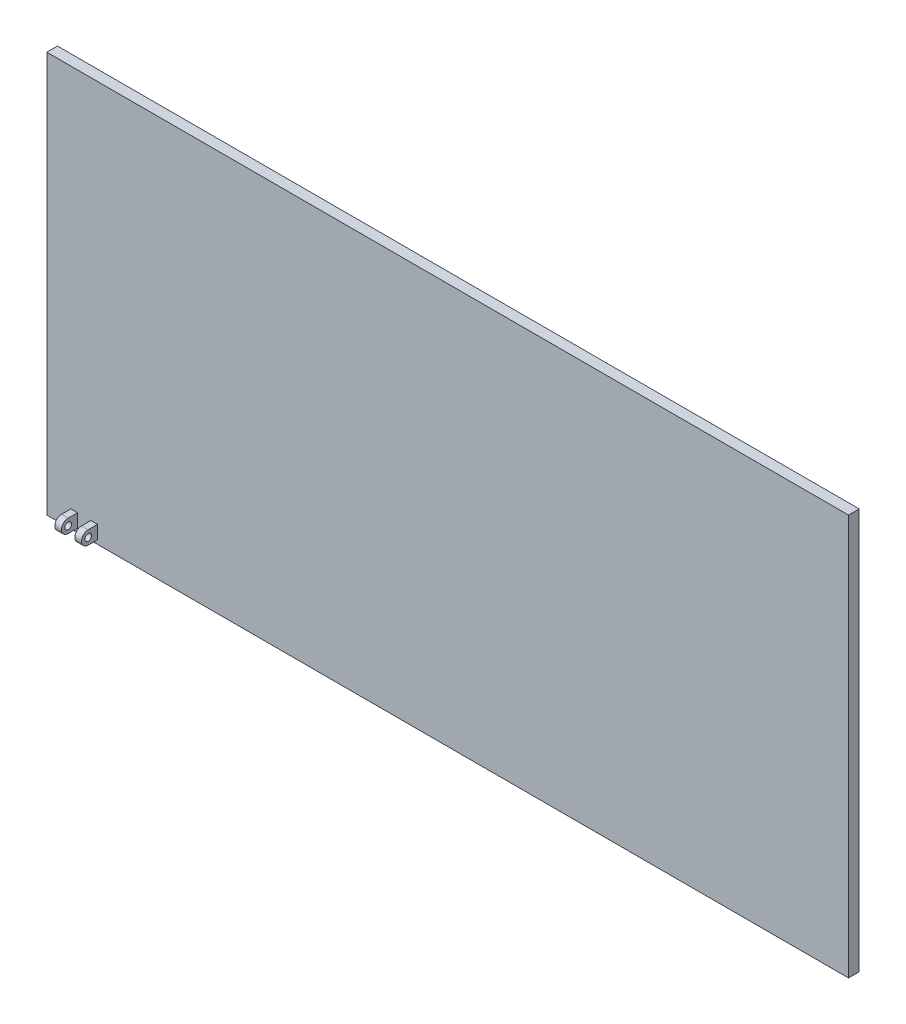
SolidWorks part; units mm, degrees
ref_plane "Plan de face" through (0, 0, 0) normal (0, 0, 1) x (1, 0, 0)
ref_plane "Plan de dessus" through (0, 0, 0) normal (0, 1, 0) x (1, 0, 0)
ref_plane "Plan de droite" through (0, 0, 0) normal (1, 0, 0) x (0, 0, -1)
sketch "Esquisse1" plane through (0, 0, 0) normal (0, 0, 1) x (1, 0, 0)
  line L1 (0, 0) -> (3000, 0)
  line L2 (0, 0) -> (0, 1500)
  line L3 (0, 1500) -> (3000, 1500)
  line L4 (3000, 0) -> (3000, 1500)
  dimension "D1" = 3000
  dimension "2000" = 1500
extrude "Boss.-Extru.1" add sketch "Esquisse1" along normal mid plane 40
sketch "Esquisse3" plane through (0, 0, 0) normal (1, 0, 0) x (0, 0, -1)
  line L0 (-20, 57.735) -> (-20, 0)
  line L1 (-20, 57.735) -> (880, -461.8802)
  line L2 (-20, 0) -> (880, -519.6152)
  line L3 (880, -461.8802) -> (880, -519.6152)
  line L4 (-20, 0) -> (-20, 1500) construction
  line L5 (-20, 0) -> (20, 0) construction
  line L6 (880, -461.8802) -> (830, -461.8802)
  line L7 (880, -461.8802) -> (880, -761.8802)
  line L8 (880, -761.8802) -> (830, -761.8802)
  line L9 (830, -461.8802) -> (830, -761.8802)
  point P12 (855, -761.8802)
  dimension "D1" = 900
  dimension "D2" = 30
  dimension "D3" = 50
  dimension "D4" = 50
  dimension "D5" = 300
extrude "Boss.-Extru.2" add sketch "Esquisse3" along normal blind 280 contours L2 L9 L8 L7 | L6 L9 L2 L3 | L9 L6 L1 L0 L2
sketch "Esquisse4" plane through (0, 0, -880) normal (0, 0, -1) x (-1, 0, 0)
  line L0 (0, -761.8802) -> (-280, -461.8802) construction
  circle A0 centre (-140, -611.8802) radius 48.3027 construction
  circle A1 centre (-140, -563.5776) radius 13.37
  circle A2 centre (-68.1687, -687.9931) radius 13.37
  circle A3 centre (-211.8313, -687.9931) radius 13.37
  point P15 (-140, -646.5212)
  dimension "D1" = 3
extrude "Enlèv. mat.-Extru.1" cut sketch "Esquisse4" against normal through all
ref_plane "Plan1" through (140, 0, 0) normal (-1, 0, 0) x (0, 0, 1)
sketch "Esquisse5" plane through (140, 0, 0) normal (-1, 0, 0) x (0, 0, 1)
  line L0 (55, 15) -> (20, 15)
  line L1 (20, 1500) -> (20, 0) construction
  line L2 (20, 15) -> (20, 65)
  line L3 (20, 65) -> (55, 65)
  circle A0 centre (55, 40) radius 12.5
  arc A1 (55, 65) -> (55, 15) centre (55, 40) cw
  dimension "D1" = 25
  dimension "D2" = 25
  dimension "D3" = 15
  dimension "D4" = 35
extrude "Boss.-Extru.3" add sketch "Esquisse5" along normal mid plane 100
sketch "Esquisse6" plane through (140, 0, 0) normal (-1, 0, 0) x (0, 0, 1)
  line L1 (20, 0) -> (93.6517, 0)
  line L2 (20, 0) -> (20, 85.9185)
  line L3 (20, 85.9185) -> (93.6517, 85.9185)
  line L4 (93.6517, 0) -> (93.6517, 85.9185)
extrude "Enlèv. mat.-Extru.2" cut sketch "Esquisse6" against normal mid plane 50
